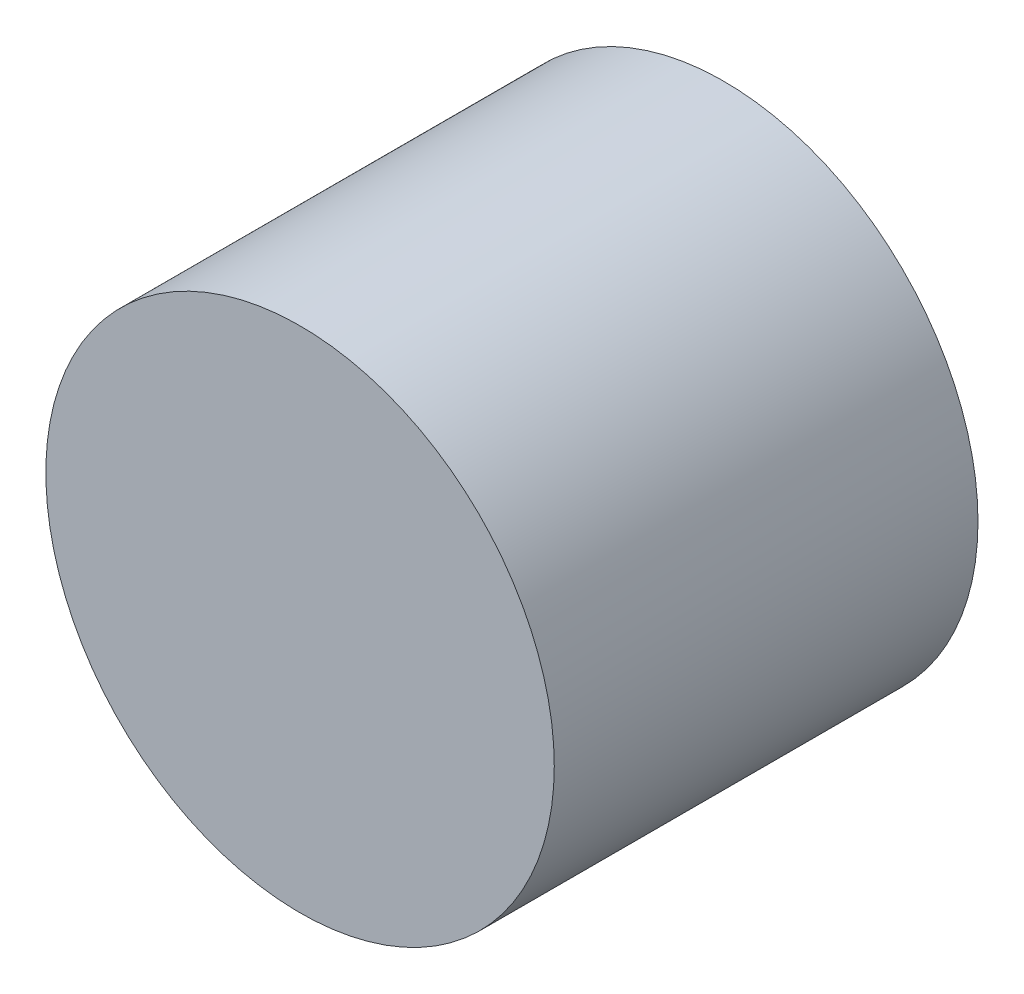
SolidWorks part; units mm, degrees
ref_plane "Plan de face" through (0, 0, 0) normal (0, 0, 1) x (1, 0, 0)
ref_plane "Plan de dessus" through (0, 0, 0) normal (0, 1, 0) x (1, 0, 0)
ref_plane "Plan de droite" through (0, 0, 0) normal (1, 0, 0) x (0, 0, -1)
sketch "Esquisse1" plane through (0, 0, 0) normal (0, 0, 1) x (1, 0, 0)
  circle A0 centre (0, 0) radius 24
  dimension "D1" = 48
extrude "Boss.-Extru.1" add sketch "Esquisse1" along normal blind 40
